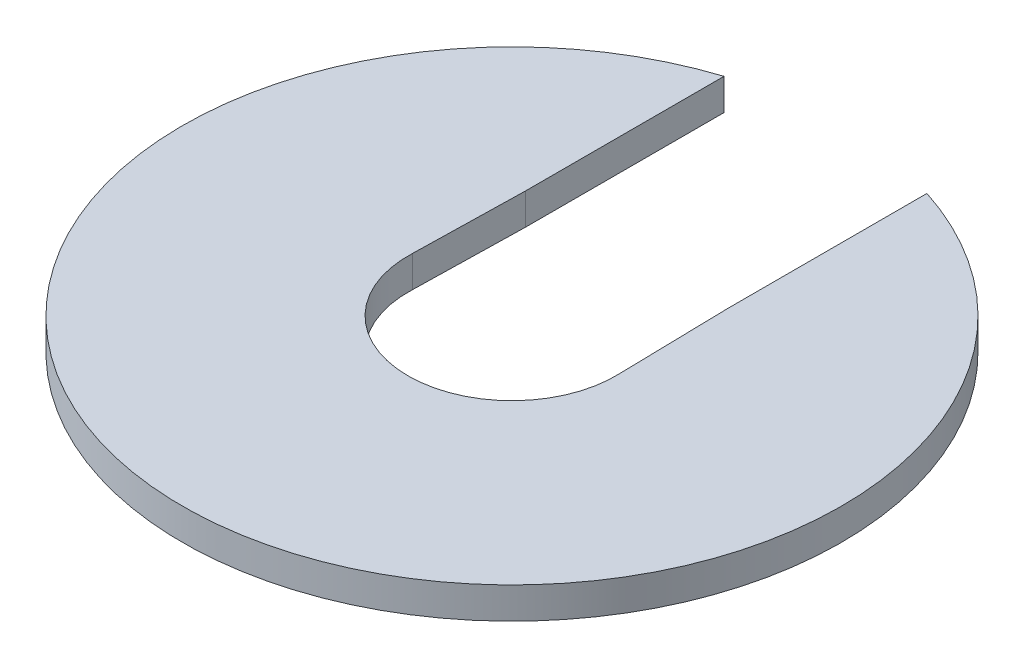
SolidWorks part; units mm, degrees
ref_plane "Front Plane" through (0, 0, 0) normal (0, 0, 1) x (1, 0, 0)
ref_plane "Top Plane" through (0, 0, 0) normal (0, 1, 0) x (1, 0, 0)
ref_plane "Right Plane" through (0, 0, 0) normal (1, 0, 0) x (0, 0, -1)
sketch "Sketch1" plane through (0, 0, 0) normal (0, 1, 0) x (1, 0, 0)
  line L0 (-10.25, 31.6832) -> (-10.25, 11.6)
  line L1 (-10.25, 11.6) -> (10.25, 11.6)
  line L2 (10.25, 11.6) -> (10.25, 31.6832)
  line L3 (-10.25, 11.6) -> (-10.5, 0)
  line L4 (10.25, 11.6) -> (10.5, 0)
  circle A0 centre (0, 0) radius 33.3
  circle A1 centre (0, 0) radius 10.5
  point P7 (0, 0)
extrude "Boss-Extrude1" add sketch "Sketch1" along normal blind 3.175 contours L0 A0 L2 L1 A1
